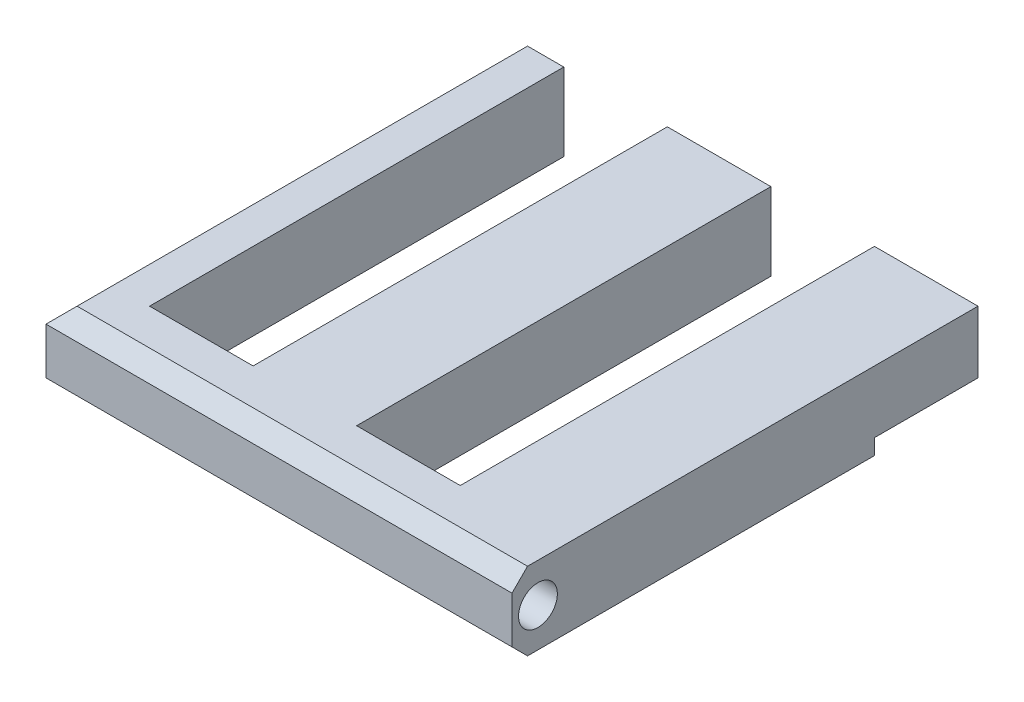
SolidWorks part; units mm, degrees
ref_plane "Front Plane" through (0, 0, 0) normal (0, 0, 1) x (1, 0, 0)
ref_plane "Top Plane" through (0, 0, 0) normal (0, 1, 0) x (1, 0, 0)
ref_plane "Right Plane" through (0, 0, 0) normal (1, 0, 0) x (0, 0, -1)
sketch "Sketch1" plane through (0, 0, 0) normal (0, 1, 0) x (1, 0, 0)
  line L0 (0, 25.4) -> (-203.2, 25.4)
  line L1 (0, 0) -> (-228.6, 0)
  line L2 (0, 0) -> (0, 228.6)
  line L3 (0, 228.6) -> (-228.6, 228.6)
  line L4 (-228.6, 0) -> (-228.6, 228.6)
  line L5 (-203.2, 25.4) -> (-203.2, 228.6)
  line L6 (-152.4, 25.4) -> (-152.4, 228.6)
  line L7 (-101.6, 25.4) -> (-101.6, 228.6)
  line L8 (-50.8, 25.4) -> (-50.8, 228.6)
  dimension "D1" = 228.6
  dimension "D2" = 228.6
  dimension "D3" = 25.4
  dimension "D4" = 50.8
  dimension "D5" = 50.8
  dimension "D6" = 50.8
extrude "Boss-Extrude2" add sketch "Sketch1" along normal blind 38.1 contours L0 L5 L3 L4 L1 L2 | L0 L7 L3 L6 | L8 L0 L2 L3
sketch "Sketch2" plane through (0, 0, -228.6) normal (0, 0, -1) x (-1, 0, 0)
  circle A0 centre (215.9, 19.05) radius 9.525
  dimension "D1" = 19.05
extrude "Cut-Extrude1" cut sketch "Sketch2" against normal blind 38.1
sketch "Sketch3" plane through (0, 0, 0) normal (1, 0, 0) x (0, 0, -1)
  circle A0 centre (12.729, 19.05) radius 9.525
  dimension "D1" = 19.05
extrude "Cut-Extrude2" cut sketch "Sketch3" against normal blind 38.1
sketch "Sketch4" plane through (0, 7.62, 0) normal (0, -1, 0) x (-1, 0, 0)
  line L0 (0, 431.8) -> (101.6, 431.8) construction
  line L1 (-177.8, 177.771) -> (76.1751, 177.771)
  line L2 (-177.8, 177.771) -> (-177.8, 431.8)
  line L3 (-177.8, 431.8) -> (76.1751, 431.8)
  line L4 (76.1751, 177.771) -> (76.1751, 431.8)
extrude "Cut-Extrude3" cut sketch "Sketch4" against normal blind 7.62
sketch "Sketch5" plane through (0, 7.62, 0) normal (0, -1, 0) x (1, 0, 0)
  line L0 (0, -431.8) -> (-101.6, -431.8) construction
  line L1 (177.8, -177.771) -> (-76.2, -177.771)
  line L2 (177.8, -177.771) -> (177.8, -431.8)
  line L3 (177.8, -431.8) -> (-76.2, -431.8)
  line L4 (-76.2, -177.771) -> (-76.2, -431.8)
  dimension "D1" = 254
extrude "Cut-Extrude4" cut sketch "Sketch5" along normal blind 60.96
sketch "Sketch6" plane through (0, 15.24, 0) normal (0, -1, 0) x (-1, 0, 0)
  line L1 (50.8, 177.771) -> (0, 177.771)
  line L2 (50.8, 177.771) -> (50.8, 228.6)
  line L3 (50.8, 228.6) -> (0, 228.6)
  line L4 (0, 177.771) -> (0, 228.6)
extrude "Boss-Extrude3" add sketch "Sketch6" along normal blind 7.62
chamfer "Chamfer1" distance 7.62 angle 45 4 edges at (-114.3, 0, 0) (-114.3, 38.1, 0) (-228.6, 0, -114.3) (-228.6, 38.1, -114.3)
